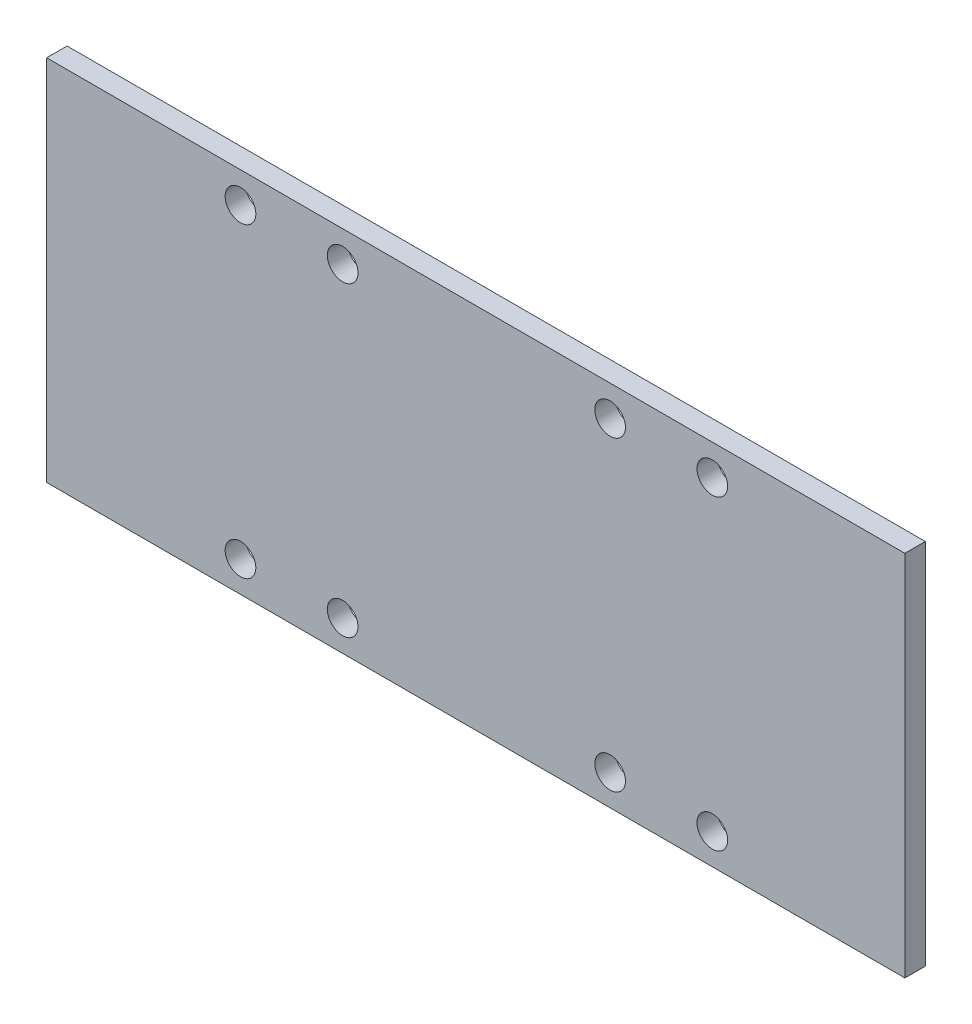
SolidWorks part; units mm, degrees
material "Thornel Mat VMA"
ref_plane "前视基准面" through (0, 0, 0) normal (0, 0, 1) x (1, 0, 0)
ref_plane "上视基准面" through (0, 0, 0) normal (0, 1, 0) x (1, 0, 0)
ref_plane "右视基准面" through (0, 0, 0) normal (1, 0, 0) x (0, 0, -1)
other "Configuration Table"
sketch "草图1" plane through (0, 0, 0) normal (0, 0, 1) x (1, 0, 0)
  line L1 (-42, 18) -> (42, 18)
  line L2 (-42, 18) -> (-42, -18)
  line L3 (-42, -18) -> (42, -18)
  line L4 (42, 18) -> (42, -18)
  line L5 (-42, 18) -> (42, -18) construction
  line L6 (-42, -18) -> (42, 18) construction
  point P0 (0, 0)
  dimension "D1" = 84
  dimension "D2" = 36
extrude "凸台-拉伸1" add sketch "草图1" along normal blind 2
sketch "草图2" plane through (0, 0, 2) normal (0, 0, 1) x (1, 0, 0)
  line L0 (-42, -18) -> (42, -18) construction
  line L1 (0, 0) -> (8.6301, 0) construction
  line L2 (42, -18) -> (42, 18) construction
  line L3 (-42, 18) -> (-42, -18) construction
  circle A0 centre (23.15, -15) radius 1.5
  circle A1 centre (13.15, -15) radius 1.5
  circle A2 centre (-13.03, -15) radius 1.5
  circle A3 centre (-23.03, -15) radius 1.5
  circle A4 centre (-23.03, 15) radius 1.5
  circle A5 centre (-13.03, 15) radius 1.5
  circle A6 centre (13.15, 15) radius 1.5
  circle A7 centre (23.15, 15) radius 1.5
  dimension "D1" = 10
  dimension "D2" = 10
  dimension "D3" = 3
  dimension "D5" = 3
  dimension "D6" = 18.85
  dimension "D7" = 18.97
  dimension "D4" = 3
extrude "切除-拉伸1" cut sketch "草图2" against normal blind 2
